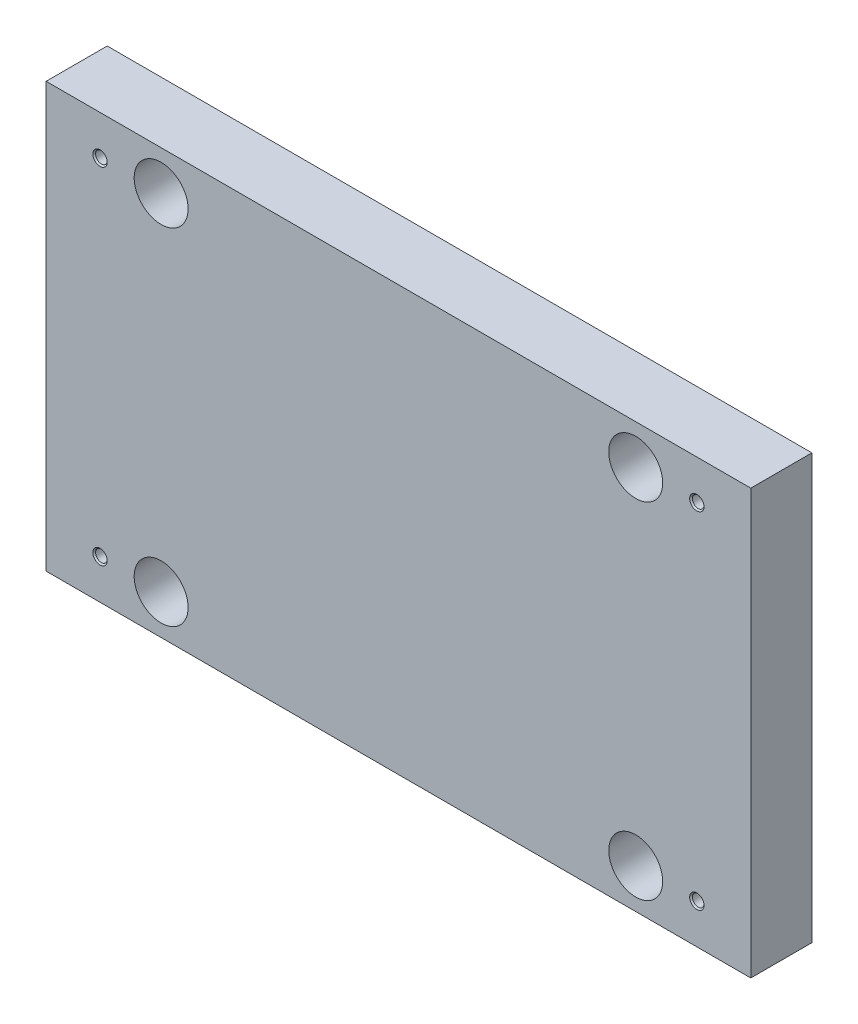
SolidWorks part; units mm, degrees
ref_plane "Спереди" through (0, 0, 0) normal (0, 0, 1) x (1, 0, 0)
ref_plane "Сверху" through (0, 0, 0) normal (0, 1, 0) x (1, 0, 0)
ref_plane "Справа" through (0, 0, 0) normal (1, 0, 0) x (0, 0, -1)
ref_plane "Плоскость4" through (0, 0, 17) normal (0, 0, 1) x (1, 0, 0)
sketch "Эскиз1" plane through (0, 0, 17) normal (0, 0, 1) x (1, 0, 0)
  line L0 (98, 59) -> (-98, 59)
  line L1 (-98, 59) -> (-98, -59)
  line L2 (-98, -59) -> (98, -59)
  line L3 (98, -59) -> (98, 59)
extrude "Бобышка-Вытянуть1" add sketch "Эскиз1" against normal blind 17
hole_wizard "Отверстие с зазором M31" positions "Эскиз3" profile "Эскиз2" hole size "M3" standard "Ansi Metric"
sketch "Эскиз3" plane through (0, 0, 17) normal (0, 0, 1) x (1, 0, 0)
  point P0 (-83, 48)
  point P1 (-83, -48)
  point P2 (83, 48)
  point P3 (83, -48)
sketch "Эскиз2" plane through (-83, 48, 17) normal (1, 0, 0) x (0, -1, 0)
  line L0 (0, 0) -> (0, 12.1547)
  line L1 (0, 12.1547) -> (1.621, 11.2188)
  line L2 (1.621, 11.2188) -> (1.621, 0)
  line L5 (1.621, 0) -> (0, 0)
  line L10 (0, 12.1547) -> (-1.621, 11.2188) construction
  line L11 (0, -6.35) -> (0, 107.95) construction
  dimension "Диаметр отверстия" = 3.242
  dimension "Глубина отверстия" = 11.2188
  dimension "Угол заточки сверла" = 120
hole_wizard "Цековка для  болта с шестигранной головкой M81" positions "Эскиз5" profile "Эскиз4" counterbore size "M8" standard "Ansi Metric"
sketch "Эскиз5" plane through (0, 0, 17) normal (0, 0, 1) x (1, 0, 0)
  point P0 (66, 48)
  point P1 (66, -48)
  point P2 (-66, 48)
  point P3 (-66, -48)
sketch "Эскиз4" plane through (66, 48, 17) normal (1, 0, 0) x (0, -1, 0)
  line L0 (0, 0) -> (0, 17)
  line L1 (0, 17) -> (4.5, 17)
  line L3 (4.5, 17) -> (4.5, 11)
  line L4 (4.5, 11) -> (7.5, 11)
  line L5 (7.5, 11) -> (7.5, 0)
  line L7 (7.5, 0) -> (0, 0)
  line L11 (0, -6.35) -> (0, 107.95) construction
  dimension "Диаметр сквозного отверстия" = 9
  dimension "Глубина сквозного отверстия" = 17
  dimension "Диаметр цековки" = 15
  dimension "Глубина цековки" = 11
chamfer "Фаска1" distance 0.379 angle 45 4 edges at (84.621, -48, 17) (84.621, 48, 17) (-81.379, 48, 17) (-81.379, -48, 17)
